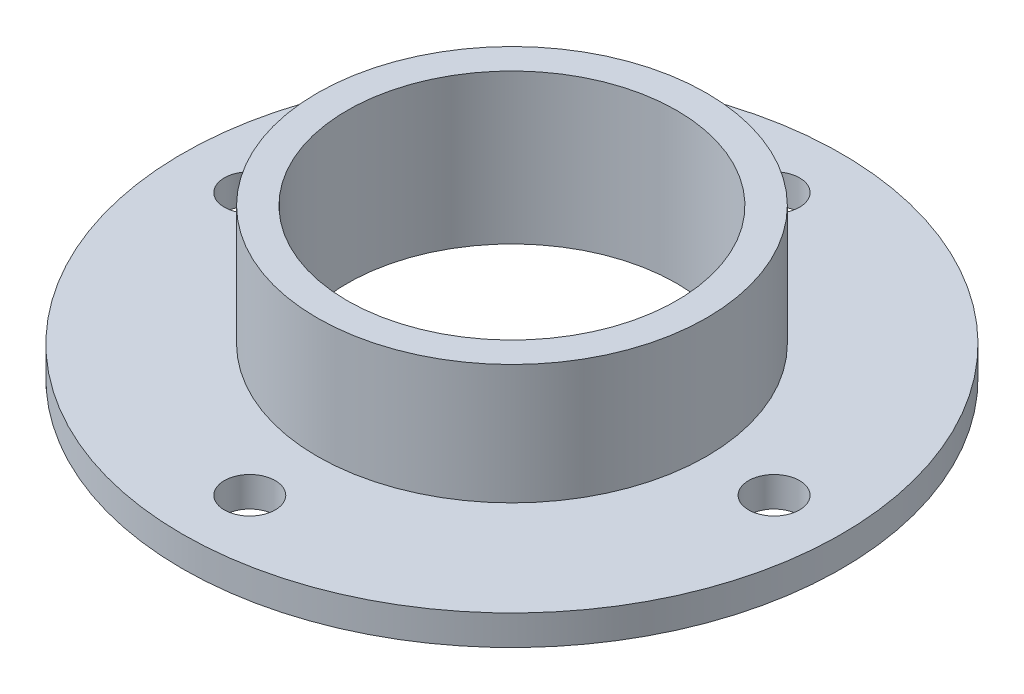
SolidWorks part; units mm, degrees
ref_plane "Front" through (0, 0, 0) normal (0, 0, 1) x (1, 0, 0)
ref_plane "Top" through (0, 0, 0) normal (0, 1, 0) x (1, 0, 0)
ref_plane "Right" through (0, 0, 0) normal (1, 0, 0) x (0, 0, -1)
sketch "Sketch1" plane through (0, 0, 0) normal (0, 0, 1) x (1, 0, 0)
  line L0 (0, 17.954) -> (0, -17.7415) construction
  line L1 (9, 0) -> (11, 0)
  line L2 (11, 0) -> (11, 8)
  line L3 (11, 8) -> (13, 8)
  line L4 (13, 8) -> (13, 0)
  line L5 (13, 0) -> (22, 0)
  line L6 (22, 0) -> (22, -2)
  line L7 (22, -2) -> (9, -2)
  line L8 (9, -2) -> (9, 0)
  dimension "D1" = 9
  dimension "D2" = 11
  dimension "D3" = 2
  dimension "D4" = 9
  dimension "D5" = 2
  dimension "D6" = 8
revolve "Revolve1" add sketch "Sketch1" angle 360 about L0
sketch "Sketch2" plane through (0, 0, 0) normal (0, 1, 0) x (1, 0, 0)
  circle A0 centre (0, 0) radius 11
extrude "Cut-Extrude1" cut sketch "Sketch2" against normal through all
ref_plane "Plane1" through (0, 17.954, 0) normal (-1, 0, 0) x (0, 0, 1)
hole_wizard "M3 Clearance Hole1" positions "Sketch5" profile "Sketch6" hole size "M3" standard "ISO" end condition through all
sketch "Sketch5" plane through (0, 0, 0) normal (0, 1, 0) x (1, 0, 0)
  circle A0 centre (0, 0) radius 17.5 construction
  circle A1 centre (0, 0) radius 22 construction
  point P0 (0, 17.5)
  point P7 (17.5, 0)
  point P9 (0, -17.5)
  point P11 (-17.5, 0)
  dimension "D1" = 4.5
  dimension "D2" = 35
sketch "Sketch6" plane through (0, 0, -17.5) normal (1, 0, 0) x (0, 0, 1)
  line L0 (0, 0) -> (0, 2)
  line L1 (0, 2) -> (1.7, 2)
  line L2 (1.7, 2) -> (1.7, 0)
  line L5 (1.7, 0) -> (0, 0)
  line L11 (0, -6.35) -> (0, 107.95) construction
  dimension "Thru Hole Dia." = 3.4
  dimension "Thru Hole Depth" = 2
